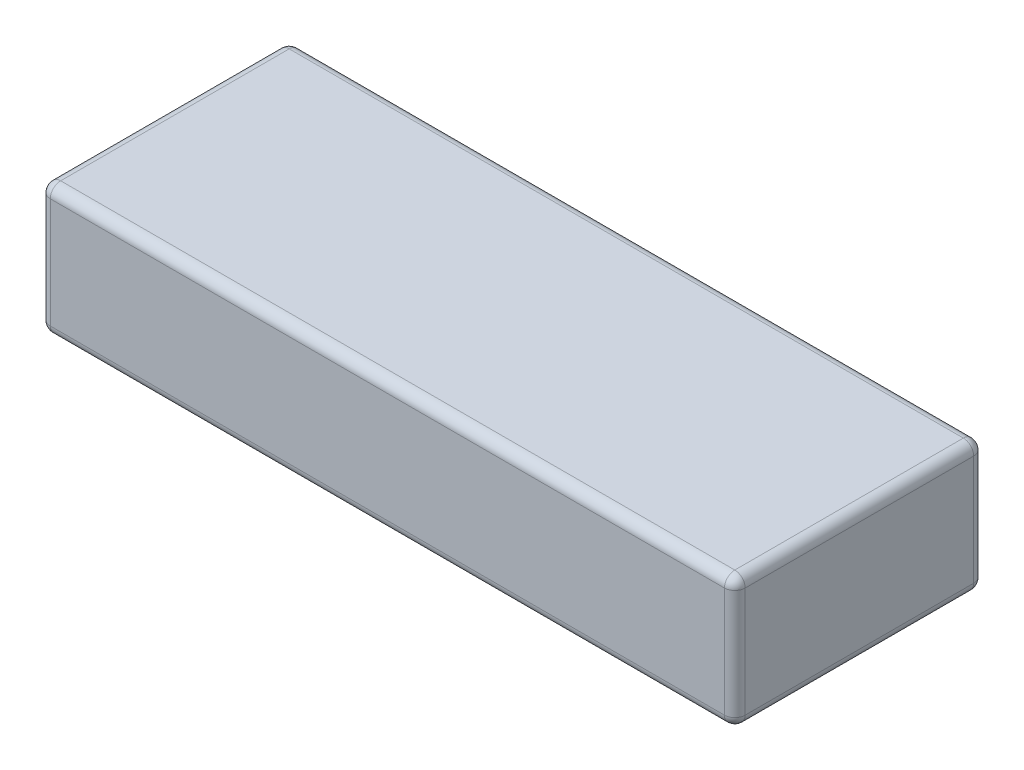
SolidWorks part; units mm, degrees
ref_plane "Front Plane" through (0, 0, 0) normal (0, 0, 1) x (1, 0, 0)
ref_plane "Top Plane" through (0, 0, 0) normal (0, 1, 0) x (1, 0, 0)
ref_plane "Right Plane" through (0, 0, 0) normal (1, 0, 0) x (0, 0, -1)
sketch "Sketch1" plane through (0, 0, 0) normal (0, 1, 0) x (1, 0, 0)
  line L1 (-84.963, 30.48) -> (84.963, 30.48)
  line L2 (-84.963, 30.48) -> (-84.963, -30.48)
  line L3 (-84.963, -30.48) -> (84.963, -30.48)
  line L4 (84.963, 30.48) -> (84.963, -30.48)
  line L5 (-84.963, 30.48) -> (84.963, -30.48) construction
  line L6 (-84.963, -30.48) -> (84.963, 30.48) construction
  point P0 (0, 0)
  dimension "D1" = 169.926
  dimension "D2" = 60.96
extrude "Boss-Extrude1" add sketch "Sketch1" along normal blind 32.004
fillet "Fillet1" radius 2.54 12 edges at (0, 0, -30.48) (-84.963, 0, 0) (-84.963, 16.002, -30.48) (-84.963, 16.002, 30.48) (0, 0, 30.48) (84.963, 0, 0) (84.963, 16.002, -30.48) (84.963, 16.002, 30.48) (84.963, 32.004, 0) (-84.963, 32.004, 0) (0, 32.004, 30.48) (0, 32.004, -30.48)
